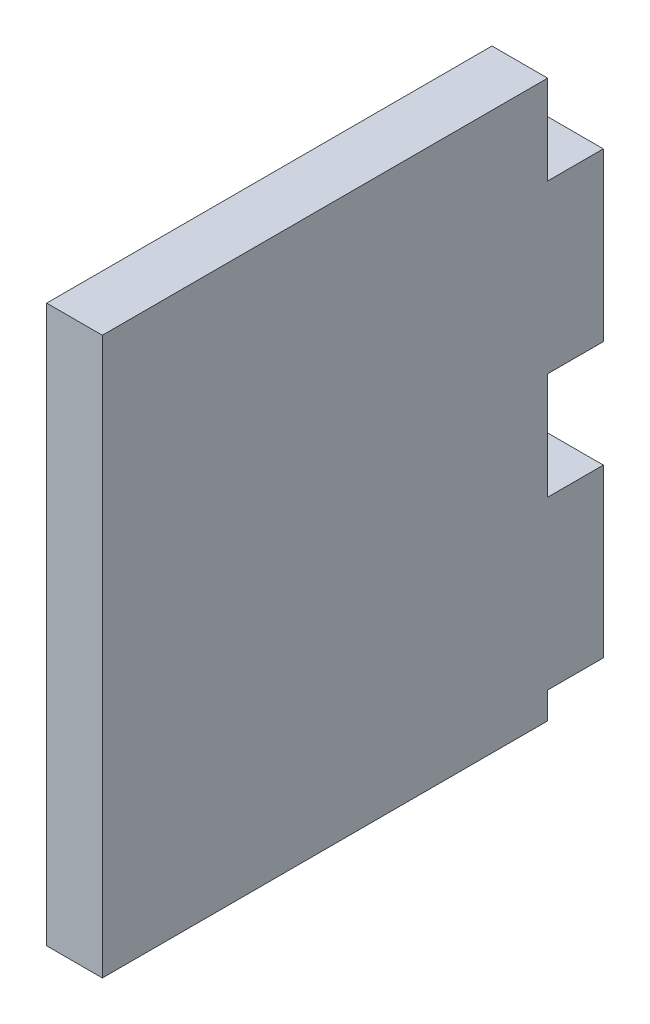
SolidWorks part; units mm, degrees
ref_plane "前视基准面" through (0, 0, 0) normal (0, 0, 1) x (1, 0, 0)
ref_plane "上视基准面" through (0, 0, 0) normal (0, 1, 0) x (1, 0, 0)
ref_plane "右视基准面" through (0, 0, 0) normal (1, 0, 0) x (0, 0, -1)
sketch "草图1" plane through (0, 0, 0) normal (1, 0, 0) x (0, 0, -1)
  line L1 (0, 0) -> (40, 0)
  line L2 (0, 0) -> (0, -50)
  line L3 (0, -50) -> (40, -50)
  line L4 (40, 0) -> (40, -50)
  line L5 (40, -8) -> (45, -8)
  line L6 (40, -8) -> (40, -23)
  line L7 (40, -23) -> (45, -23)
  line L8 (45, -8) -> (45, -23)
  line L9 (40, -32.6) -> (45, -32.6)
  line L10 (40, -32.6) -> (40, -47.6)
  line L11 (40, -47.6) -> (45, -47.6)
  line L12 (45, -32.6) -> (45, -47.6)
  dimension "D1" = 50
  dimension "D2" = 40
  dimension "D3" = 5
  dimension "D4" = 5
  dimension "D5" = 9.6
  dimension "D6" = 15
  dimension "D7" = 15
  dimension "D8" = 8
extrude "凸台-拉伸1" add sketch "草图1" along normal blind 5 contours L4 L1 L2 L3 | L8 L5 L4 L7 | L12 L9 L4 L11
